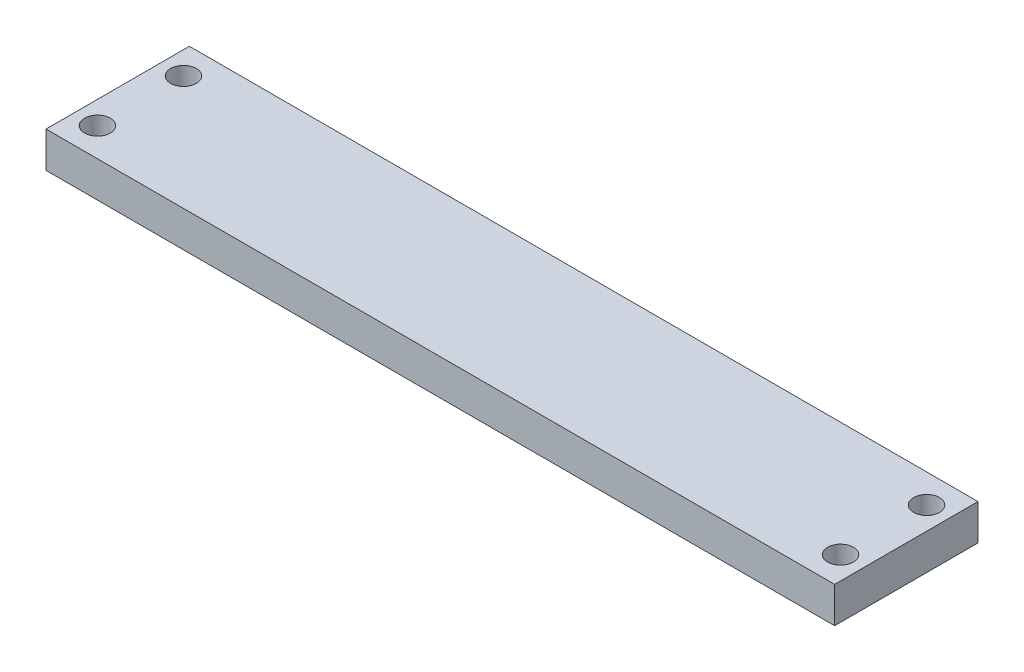
SolidWorks part; units mm, degrees
ref_plane "Front Plane" through (0, 0, 0) normal (0, 0, 1) x (1, 0, 0)
ref_plane "Top Plane" through (0, 0, 0) normal (0, 1, 0) x (1, 0, 0)
ref_plane "Right Plane" through (0, 0, 0) normal (1, 0, 0) x (0, 0, -1)
sketch "Sketch1" plane through (0, 0, 0) normal (0, 1, 0) x (1, 0, 0)
  line L5 (-55, -10) -> (55, -10)
  line L6 (-55, -10) -> (-55, 10)
  line L7 (-55, 10) -> (55, 10)
  line L8 (55, -10) -> (55, 10)
  line L9 (0, 10) -> (0, -10) construction
  line L10 (-55, 0) -> (55, 0) construction
  point P0 (0, 0)
  dimension "D1" = 20
  dimension "D2" = 110
extrude "Boss-Extrude1" add sketch "Sketch1" along normal mid plane 5
sketch "Sketch2" plane through (0, 2.5, 0) normal (0, 1, 0) x (1, 0, 0)
  line L0 (0, 10) -> (0, -10) construction
  line L1 (55, 10) -> (-55, 10) construction
  line L2 (-55, -10) -> (55, -10) construction
  line L3 (-55, 0) -> (55, 0) construction
  line L4 (-55, 10) -> (-55, -10) construction
  line L5 (55, -10) -> (55, 10) construction
  point P12 (-51.825, -6)
  point P14 (51.825, -6)
  point P16 (-51.825, 6)
  point P17 (51.825, 6)
  dimension "D1" = 103.65
  dimension "D2" = 4
hole_wizard "M3 Clearance Hole1" positions "Sketch2" profile "Sketch3" hole size "M3" standard "ANSI Metric" end condition through all
sketch "Sketch3" plane through (51.825, 2.5, -6) normal (1, 0, 0) x (0, 0, 1)
  line L0 (0, 0) -> (0, 5)
  line L1 (0, 5) -> (1.8, 5)
  line L2 (1.8, 5) -> (1.8, 0)
  line L5 (1.8, 0) -> (0, 0)
  line L11 (0, -6.35) -> (0, 107.95) construction
  dimension "Thru Hole Dia." = 3.6
  dimension "Thru Hole Depth" = 5
